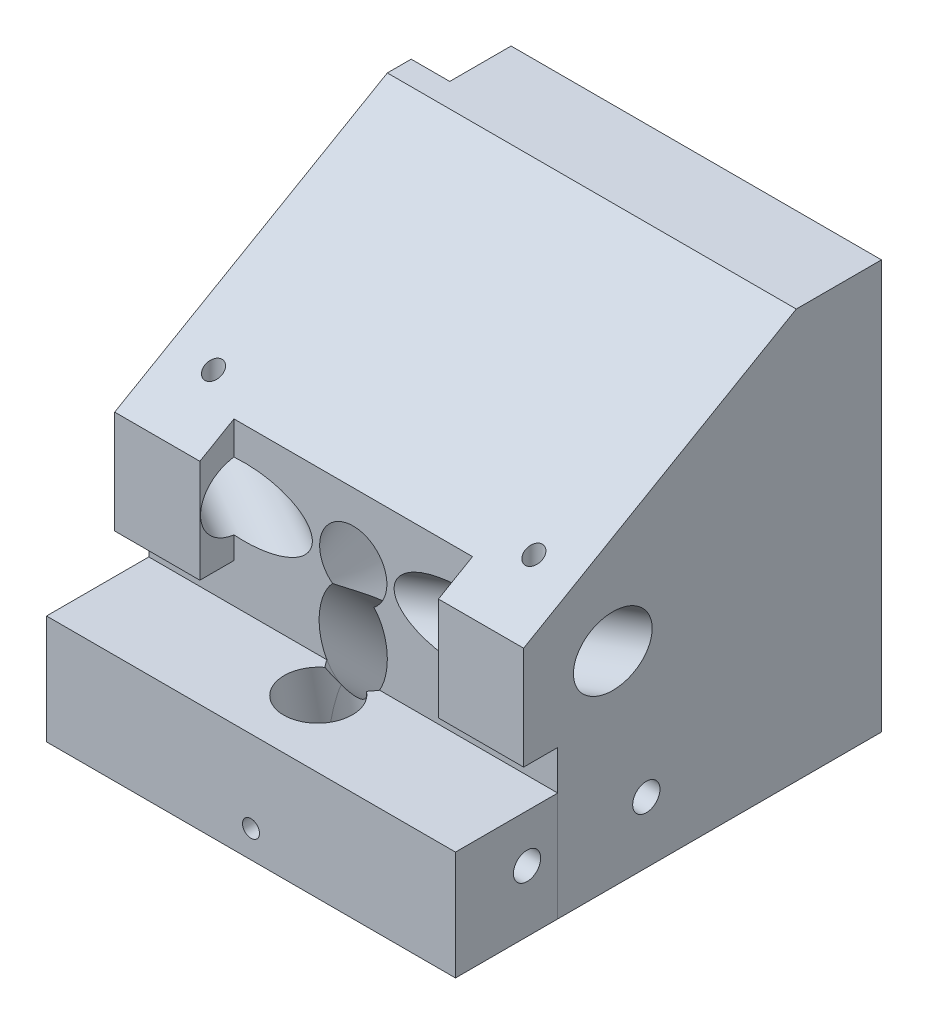
SolidWorks part; units mm, degrees
material "SKD11淬火HRC56-60"
ref_plane "前基準面" through (0, 0, 0) normal (0, 0, 1) x (1, 0, 0)
ref_plane "上基準面" through (0, 0, 0) normal (0, 1, 0) x (1, 0, 0)
ref_plane "右基準面" through (0, 0, 0) normal (1, 0, 0) x (0, 0, -1)
sketch "草图1" plane through (0, 0, 0) normal (0, 0, 1) x (1, 0, 0)
  line L1 (0, 0) -> (120, 0)
  line L2 (0, 0) -> (0, 120)
  line L3 (0, 120) -> (120, 120)
  line L4 (120, 0) -> (120, 120)
  dimension "D1" = 120
  dimension "D2" = 120
extrude "凸台-拉伸1" add sketch "草图1" along normal blind 95
sketch "草图2" plane through (0, 0, 0) normal (0, 0, -1) x (-1, 0, 0)
  line L0 (-60, 0) -> (-60, 120) construction
  line L1 (0, 0) -> (-120, 0) construction
  line L2 (-120, 120) -> (0, 120) construction
  circle A0 centre (-60, 60) radius 47.15
  dimension "D1" = 94.3
extrude "切除-拉伸2" cut sketch "草图2" against normal blind 18
sketch "草图4" plane through (0, 0, 18) normal (0, 0, -1) x (-1, 0, 0)
  circle A0 centre (-60, 60) radius 44.15
  circle A1 centre (-60, 60) radius 47.15 construction
  dimension "D1" = 3
extrude "切除-拉伸3" cut sketch "草图4" against normal through all draft 24
chamfer "倒角1" distance 70 angle 30 1 edges at (60, 120, 95)
sketch "草图5" plane through (0, 0, 0) normal (0, 0, -1) x (-1, 0, 0)
  line L0 (-60, 60) -> (-7.4752, 112.5248) construction
  line L1 (-60, 60) -> (10.2926, 60) construction
  line L2 (-40.9081, 90.4056) -> (3.8231, 135.1369)
  line L3 (3.8231, 135.1369) -> (15.1369, 123.8231)
  line L4 (15.1369, 123.8231) -> (-29.5944, 79.0919)
  line L5 (-29.5944, 79.0919) -> (-40.9081, 90.4056)
  dimension "D1" = 45
  dimension "D2" = 16
  dimension "D3" = 63.2596
  dimension "D4" = 35
extrude "切除-拉伸4" cut sketch "草图5" against normal up to surface (18 mm away) up to face at (15.85, 60, 18)
ref_plane "基准面1" through (48.8638, 0, -28.2115) normal (0.866, 0, -0.5) x (-0.5, 0, -0.866)
sketch "草图6" plane through (48.8638, 0, -28.2115) normal (0.866, 0, -0.5) x (-0.5, 0, -0.866)
  line L0 (-104.028, 60) -> (-167.9795, 60) construction
  line L1 (-142.2724, 0) -> (-142.2724, 79.5855) construction
  line L2 (-82.2724, 0) -> (-142.2724, 0) construction
  circle A0 centre (-128.2724, 60) radius 10
  dimension "D1" = 20
  dimension "D2" = 14
  dimension "D3" = 60
extrude "切除-拉伸5" cut sketch "草图6" against normal through all and the other way through all
ref_plane "基准面2" through (41.1362, 0, 23.75) normal (-0.866, 0, -0.5) x (-0.5, 0, 0.866)
sketch "草图7" plane through (41.1362, 0, 23.75) normal (-0.866, 0, -0.5) x (-0.5, 0, 0.866)
  line L0 (10.3223, 60) -> (94.9758, 60) construction
  line L1 (82.2724, 0) -> (22.2724, 0) construction
  line L2 (82.2724, 79.5855) -> (82.2724, 0) construction
  circle A0 centre (68.2724, 60) radius 10
  dimension "D2" = 14
  dimension "D3" = 20
  dimension "D1" = 60
extrude "切除-拉伸6" cut sketch "草图7" against normal through all and the other way through all
sketch "草图9" plane through (0, 0, 95) normal (0, 0, 1) x (1, 0, 0)
  line L0 (120, 0) -> (120, 79.5855) construction
  line L1 (0, 0) -> (120, 0)
  line L2 (0, 0) -> (0, 32)
  line L3 (0, 32) -> (120, 32)
  line L4 (120, 0) -> (120, 32)
  dimension "D1" = 32
extrude "凸台-拉伸2" add sketch "草图9" along normal blind 30 separate body
ref_plane "基准面3" through (0, 47.5, 47.5) normal (0, 0.7071, 0.7071) x (1, 0, 0)
sketch "草图8" plane through (0, 47.5, 47.5) normal (0, 0.7071, 0.7071) x (1, 0, 0)
  line L0 (60, -67.1751) -> (60, 22.703) construction
  line L1 (0, -67.1751) -> (120, -67.1751) construction
  circle A0 centre (60, -38.1751) radius 10
  dimension "D1" = 20
  dimension "D2" = 29
extrude "切除-拉伸7" cut sketch "草图8" along normal through all and the other way through all
sketch "草图11" plane through (0, 47.5, 47.5) normal (0, 0.7071, 0.7071) x (1, 0, 0)
  line L0 (66.0863, -30.2406) -> (53.9137, -30.2406)
  arc A0 (53.9137, -30.2406) -> (66.0863, -30.2406) centre (60, -38.1751) ccw construction
  arc A1 (53.9137, -30.2406) -> (66.0863, -30.2406) centre (60, -38.1751) ccw
extrude "切除-拉伸8" cut sketch "草图11" along normal through all
sketch "草图14" plane through (0, 0, 95) normal (0, 0, 1) x (1, 0, 0)
  line L0 (60, 79.5855) -> (60, 71.0888) construction
  line L1 (120, 79.5855) -> (95, 79.5855)
  line L2 (120, 79.5855) -> (120, 43.5855)
  line L3 (120, 43.5855) -> (95, 43.5855)
  line L4 (95, 79.5855) -> (95, 43.5855)
  line L5 (120, 79.5855) -> (0, 79.5855) construction
  line L6 (25, 79.5855) -> (25, 43.5855)
  line L7 (0, 43.5855) -> (25, 43.5855)
  line L8 (0, 79.5855) -> (0, 43.5855)
  line L9 (0, 79.5855) -> (25, 79.5855)
  dimension "D1" = 25
  dimension "D2" = 36
extrude "凸台-拉伸3" add sketch "草图14" along normal blind 10
sketch "草图15" plane through (48.8638, 0, -28.2115) normal (0.866, 0, -0.5) x (-0.5, 0, -0.866)
  line L1 (-129.7724, 50.1131) -> (-129.7724, 69.8869)
  line L2 (-129.7724, 50.1131) -> (-129.7724, 69.8869)
  arc A1 (-129.7724, 69.8869) -> (-129.7724, 50.1131) centre (-128.2724, 60) ccw
  arc A2 (-129.7724, 69.8869) -> (-129.7724, 50.1131) centre (-128.2724, 60) ccw
  dimension "D1" = 0
extrude "切除-拉伸11" cut sketch "草图15" against normal through all
sketch "草图16" plane through (41.1362, 0, 23.75) normal (-0.866, 0, -0.5) x (-0.5, 0, 0.866)
  line L1 (69.7724, 69.8869) -> (69.7724, 50.1131)
  line L2 (69.7724, 69.8869) -> (69.7724, 50.1131)
  arc A1 (69.7724, 50.1131) -> (69.7724, 69.8869) centre (68.2724, 60) ccw
  arc A2 (69.7724, 50.1131) -> (69.7724, 69.8869) centre (68.2724, 60) ccw
  dimension "D1" = 0
extrude "切除-拉伸12" cut sketch "草图16" against normal through all
sketch "草图17" plane through (120, 0, 0) normal (1, 0, 0) x (0, 0, -1)
  line L0 (-95, 79.5855) -> (-114.0319, 68.5974)
  line L1 (-114.0319, 68.5974) -> (-114.0319, 79.5855)
  line L2 (-95, 79.5855) -> (-114.0319, 79.5855)
  line L3 (-25, 120) -> (-95, 79.5855) construction
extrude "切除-拉伸13" cut sketch "草图17" against normal through all
ref_plane "基准面4" through (0, 21.3763, 3.7692) normal (0, -0.9848, -0.1736) x (1, 0, 0)
sketch "草图12" plane through (0, 21.3763, 3.7692) normal (0, -0.9848, -0.1736) x (1, 0, 0)
  line L0 (60, 123.101) -> (60, 77.527) construction
  line L1 (0, 123.101) -> (120, 123.101) construction
  circle A0 centre (60, 98.101) radius 10
  dimension "D1" = 20
  dimension "D2" = 25
extrude "切除-拉伸9" cut sketch "草图12" against normal through all and the other way through all
sketch "草图13" plane through (0, 21.3763, 3.7692) normal (0, -0.9848, -0.1736) x (1, 0, 0)
  circle A3 centre (60, 98.101) radius 10
extrude "切除-拉伸10" cut sketch "草图13" against normal through all and the other way through all
hole_wizard "M6 螺纹孔1" positions "草图19" profile "草图18" tap size "M6" standard "ISO"
sketch "草图19" plane through (0, 0, 0) normal (0, -1, 0) x (1, 0, 0)
  point P0 (110, 12.5)
  point P1 (110, 82.5)
  point P4 (10, 82.5)
  point P7 (10, 12.5)
sketch "草图18" plane through (110, 0, 12.5) normal (1, 0, 0) x (0, 0, -1)
  line L0 (0, 0) -> (0, 16.5022)
  line L1 (0, 16.5022) -> (2.5, 15)
  line L2 (2.5, 15) -> (2.5, 0)
  line L5 (2.5, 0) -> (0, 0)
  line L10 (0, 16.5022) -> (-2.5, 15) construction
  line L11 (0, -6.35) -> (0, 107.95) construction
  dimension "螺纹孔钻头直径" = 5
  dimension "螺纹孔钻头深度" = 15
  dimension "导头角度" = 118
cosmetic thread "孔螺蚊线1" parameters "D1"=12, "D2"=6
cosmetic thread "孔螺蚊线2" parameters "D1"=12, "D2"=6
cosmetic thread "孔螺蚊线3" parameters "D1"=12, "D2"=6
cosmetic thread "孔螺蚊线4" parameters "D1"=12, "D2"=6
hole_wizard "M6 螺纹孔2" positions "草图21" profile "草图20" tap size "M6" standard "ISO"
sketch "草图21" plane through (0, 120, 0) normal (0, 1, 0) x (-1, 0, 0)
  line L0 (-60, 95) -> (-60, 25) construction
  line L1 (-95, 95) -> (-25, 95) construction
  line L2 (0, 25) -> (-120, 25) construction
  line L3 (-120, 105) -> (-95, 105) construction
  point P1 (-107, 89)
  point P3 (-13, 89)
  dimension "D1" = 16
  dimension "D2" = 94
sketch "草图20" plane through (107, 120, 89) normal (1, 0, 0) x (0, 0, 1)
  line L0 (0, 0) -> (0, 66.5022)
  line L1 (0, 66.5022) -> (2.5, 65)
  line L2 (2.5, 65) -> (2.5, 0)
  line L5 (2.5, 0) -> (0, 0)
  line L10 (0, 66.5022) -> (-2.5, 65) construction
  line L11 (0, -6.35) -> (0, 107.95) construction
  dimension "螺纹孔钻头直径" = 5
  dimension "螺纹孔钻头深度" = 65
  dimension "导头角度" = 118
cosmetic thread "孔螺蚊线5" parameters "D1"=51.2294, "D2"=6
cosmetic thread "孔螺蚊线6" parameters "D1"=51.2294, "D2"=6
hole_wizard "M6 螺纹孔3" positions "草图23" profile "草图22" tap size "M6" standard "ISO"
sketch "草图23" plane through (0, 0, 125) normal (0, 0, 1) x (1, 0, 0)
  line L0 (60, 0) -> (60, 18.337) construction
  line L1 (0, 0) -> (120, 0) construction
  point P0 (60, 8)
  dimension "D1" = 8
sketch "草图22" plane through (60, 8, 125) normal (1, 0, 0) x (0, -1, 0)
  line L0 (0, 0) -> (0, 19.5022)
  line L1 (0, 19.5022) -> (2.5, 18)
  line L2 (2.5, 18) -> (2.5, 0)
  line L5 (2.5, 0) -> (0, 0)
  line L10 (0, 19.5022) -> (-2.5, 18) construction
  line L11 (0, -6.35) -> (0, 107.95) construction
  dimension "螺纹孔钻头直径" = 5
  dimension "螺纹孔钻头深度" = 18
  dimension "导头角度" = 118
cosmetic thread "孔螺蚊线7" parameters "D1"=14.2926, "D2"=6
sketch "草图24" plane through (120, 0, 0) normal (1, 0, 0) x (0, 0, -1)
  line L0 (-125, 0) -> (-125, 32) construction
  line L1 (-125, 0) -> (-95, 0) construction
  circle A0 centre (-104, 18) radius 4
  circle A1 centre (-69, 18) radius 4
  dimension "D1" = 8
  dimension "D2" = 21
  dimension "D3" = 35
  dimension "D4" = 18
extrude "切除-拉伸14" cut sketch "草图24" against normal blind 30
hole_wizard "M6 螺纹孔4" positions "草图26" profile "草图25" tap size "M6" standard "ISO"
sketch "草图26" plane through (90, 0, 0) normal (1, 0, 0) x (0, 0, -1)
  point P0 (-69, 18)
  point P1 (-104, 18)
sketch "草图25" plane through (90, 18, 69) normal (0, 1, 0) x (0, 0, -1)
  line L0 (0, 0) -> (0, 36.5022)
  line L1 (0, 36.5022) -> (2.5, 35)
  line L2 (2.5, 35) -> (2.5, 0)
  line L5 (2.5, 0) -> (0, 0)
  line L10 (0, 36.5022) -> (-2.5, 35) construction
  line L11 (0, -6.35) -> (0, 107.95) construction
  dimension "螺纹孔钻头直径" = 5
  dimension "螺纹孔钻头深度" = 35
  dimension "导头角度" = 118
cosmetic thread "孔螺蚊线8" parameters "D1"=21.758, "D2"=6
cosmetic thread "孔螺蚊线9" parameters "D1"=30, "D2"=6
hole_wizard "M5 螺纹孔1" positions "草图28" profile "草图27" tap size "M5" standard "ISO"
sketch "草图28" plane through (0, 0, 0) normal (0, 0, -1) x (-1, 0, 0)
  line L0 (-60, 107.15) -> (-60, 12.85) construction
  line L1 (-60, 60) -> (-112.2279, 7.7721) construction
  line L2 (-60, 60) -> (-9.0816, 9.0816) construction
  line L3 (-60, 60) -> (-110.5394, 110.5394) construction
  line L4 (-60, 60) -> (-28.5922, 114.3999) construction
  arc A0 (-32.8002, 98.5135) -> (-21.4865, 87.1998) centre (-60, 60) ccw construction
  circle A1 centre (-60, 60) radius 52.5
  point P0 (-33.75, 105.4663)
  point P1 (-97.1231, 97.1231)
  point P3 (-97.1231, 22.8769)
  point P5 (-22.8769, 22.8769)
  dimension "D5" = 105
  dimension "D1" = 45
  dimension "D2" = 45
  dimension "D3" = 30
  dimension "D4" = 45
sketch "草图27" plane through (33.75, 105.4663, 0) normal (1, 0, 0) x (0, 1, 0)
  line L0 (0, 0) -> (0, 13.6618)
  line L1 (0, 13.6618) -> (2.1, 12.4)
  line L2 (2.1, 12.4) -> (2.1, 0)
  line L5 (2.1, 0) -> (0, 0)
  line L10 (0, 13.6618) -> (-2.1, 12.4) construction
  line L11 (0, -6.35) -> (0, 107.95) construction
  dimension "螺纹孔钻头直径" = 4.2
  dimension "螺纹孔钻头深度" = 12.4
  dimension "导头角度" = 118
cosmetic thread "孔螺蚊线10" parameters "D1"=10, "D2"=5
cosmetic thread "孔螺蚊线11" parameters "D1"=10, "D2"=5
cosmetic thread "孔螺蚊线12" parameters "D1"=10, "D2"=5
cosmetic thread "孔螺蚊线13" parameters "D1"=10, "D2"=5
